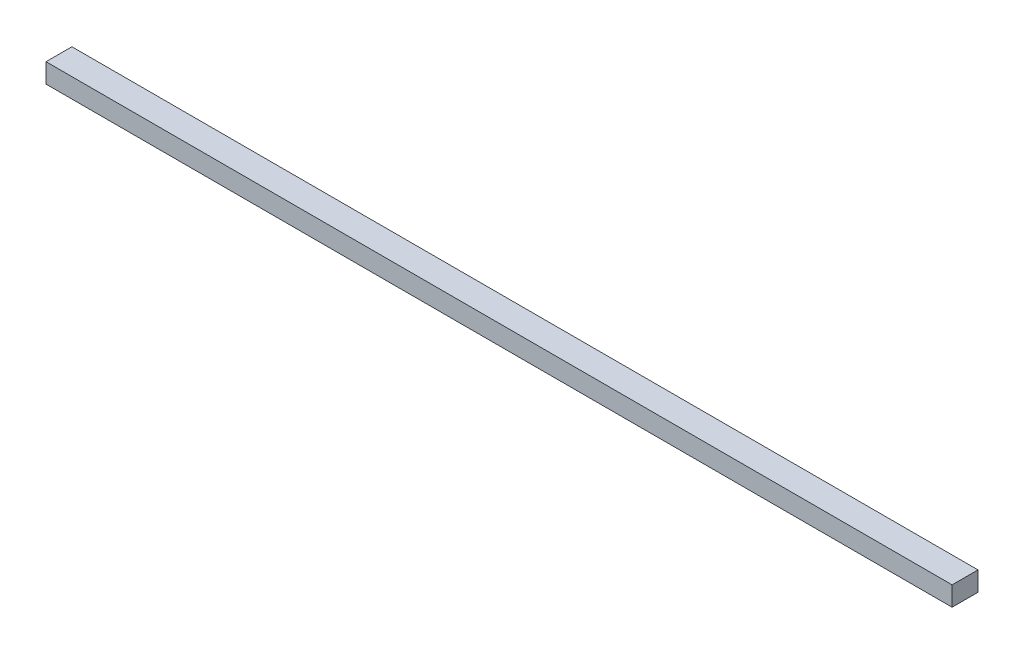
SolidWorks part; units mm, degrees
material "Titanium"
ref_plane "Front Plane" through (0, 0, 0) normal (0, 0, 1) x (1, 0, 0)
ref_plane "Top Plane" through (0, 0, 0) normal (0, 1, 0) x (1, 0, 0)
ref_plane "Right Plane" through (0, 0, 0) normal (1, 0, 0) x (0, 0, -1)
sketch "Sketch1" plane through (0, 0, 0) normal (0, 1, 0) x (1, 0, 0)
  line L1 (-140, -4) -> (140, -4)
  line L2 (-140, -4) -> (-140, 4)
  line L3 (-140, 4) -> (140, 4)
  line L4 (140, -4) -> (140, 4)
  line L5 (-140, -4) -> (140, 4) construction
  line L6 (-140, 4) -> (140, -4) construction
  point P0 (0, 0)
  dimension "D1" = 280
  dimension "D2" = 8
extrude "Boss-Extrude1" add sketch "Sketch1" along normal blind 6
